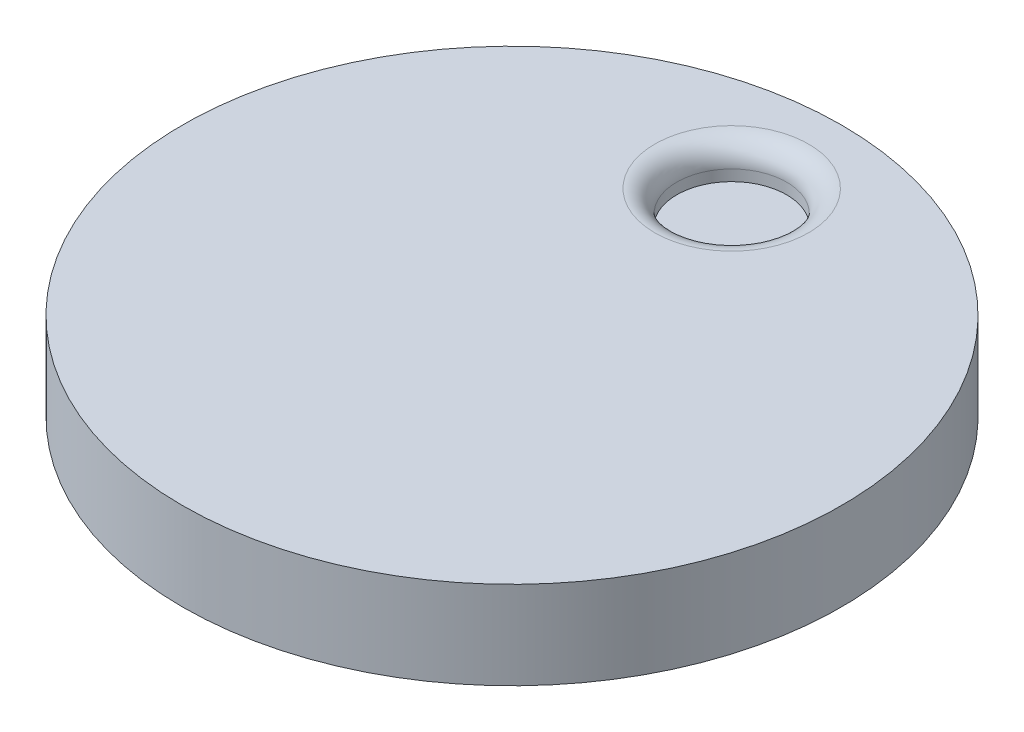
SolidWorks part; units mm, degrees
ref_plane "Alzado" through (0, 0, 0) normal (0, 0, 1) x (1, 0, 0)
ref_plane "Planta" through (0, 0, 0) normal (0, 1, 0) x (1, 0, 0)
ref_plane "Vista lateral" through (0, 0, 0) normal (1, 0, 0) x (0, 0, -1)
sketch "Croquis1" plane through (0, 0, 0) normal (0, 1, 0) x (1, 0, 0)
  circle A0 centre (0, 0) radius 30
  dimension "D1" = 60
extrude "Saliente-Extruir1" add sketch "Croquis1" along normal blind 8
sketch "Croquis2" plane through (0, 8, 0) normal (0, 1, 0) x (1, 0, 0)
  circle A0 centre (0, 20) radius 5
  dimension "D1" = 10
  dimension "D2" = 20
extrude "Cortar-Extruir1" cut sketch "Croquis2" against normal blind 3
fillet "Redondeo1" radius 2 1 edges at (0, 8, -15)
